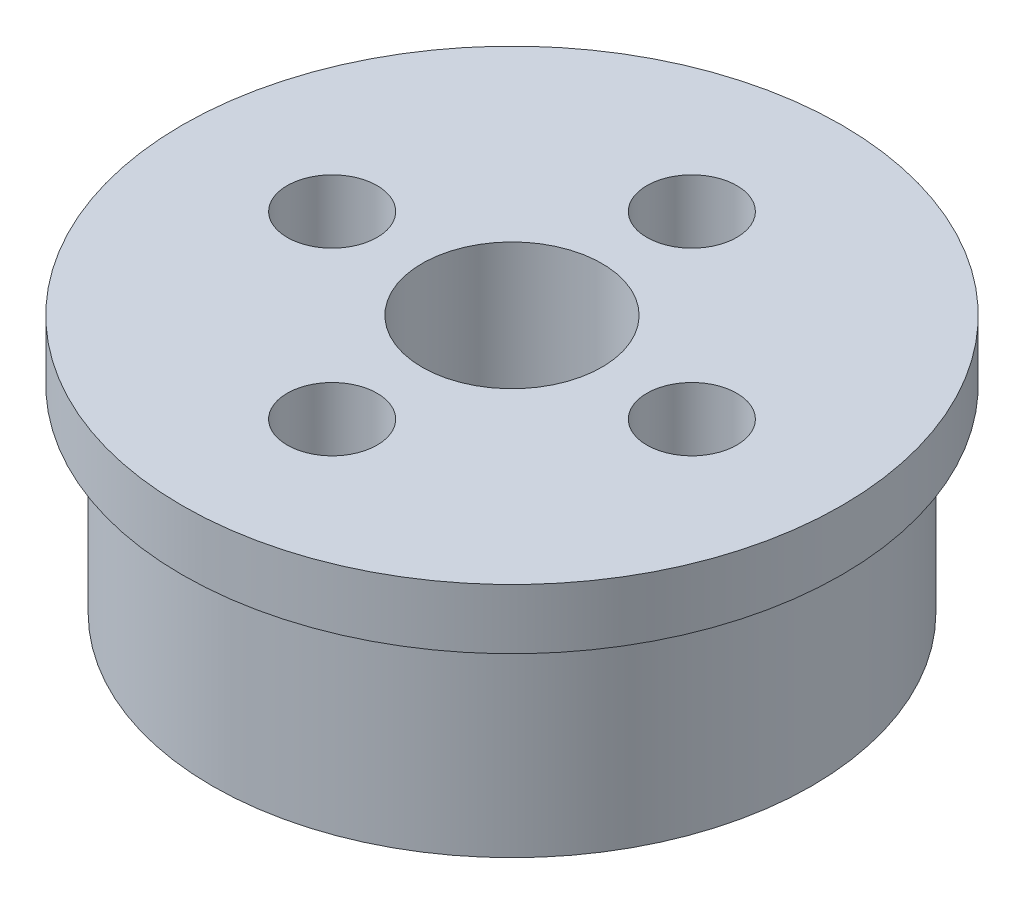
SolidWorks part; units mm, degrees
ref_plane "前视基准面" through (0, 0, 0) normal (0, 0, 1) x (1, 0, 0)
ref_plane "上视基准面" through (0, 0, 0) normal (0, 1, 0) x (1, 0, 0)
ref_plane "右视基准面" through (0, 0, 0) normal (1, 0, 0) x (0, 0, -1)
sketch "草图1" plane through (0, 0, 0) normal (0, 1, 0) x (1, 0, 0)
  circle A0 centre (0, 0) radius 10
  circle A1 centre (0, 0) radius 3
  dimension "D1" = 20
  dimension "D2" = 6
extrude "凸台-拉伸1" add sketch "草图1" along normal blind 6.6
sketch "草图2" plane through (0, 6.6, 0) normal (0, 1, 0) x (1, 0, 0)
  circle A0 centre (0, 0) radius 11
  circle A2 centre (0, 0) radius 3 construction
  circle A3 centre (0, 0) radius 3
  dimension "D1" = 22
extrude "凸台-拉伸2" add sketch "草图2" along normal blind 2
sketch "草图3" plane through (0, 0, 0) normal (0, -1, 0) x (1, 0, 0)
  line L0 (0, 10) -> (0, 3) construction
  circle A0 centre (0, 6) radius 1.5
  circle A1 centre (0, 0) radius 10 construction
  circle A2 centre (0, 0) radius 10 construction
  circle A3 centre (0, 0) radius 3 construction
  dimension "D1" = 3
  dimension "D2" = 6
extrude "切除-拉伸1" cut sketch "草图3" against normal up to next
pattern_circular "阵列(圆周)1" count 4 over 360 about axis through (0, 0, 0) along (0, 1, 0) of "切除-拉伸1"
